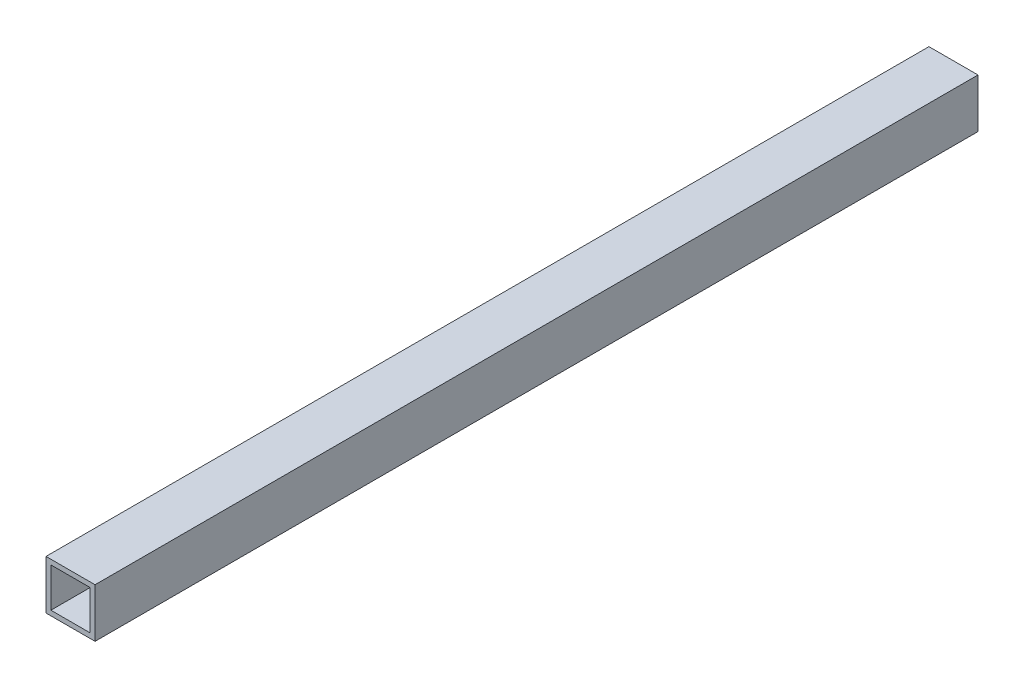
SolidWorks part; units mm, degrees
ref_plane "Płaszczyzna przednia" through (0, 0, 0) normal (0, 0, 1) x (1, 0, 0)
ref_plane "Płaszczyzna górna" through (0, 0, 0) normal (0, 1, 0) x (1, 0, 0)
ref_plane "Płaszczyzna prawa" through (0, 0, 0) normal (1, 0, 0) x (0, 0, -1)
sketch "Szkic1" plane through (0, 0, 0) normal (0, 0, 1) x (1, 0, 0)
  line L1 (-5, -5) -> (5, -5)
  line L2 (-5, -5) -> (-5, 5)
  line L3 (-5, 5) -> (5, 5)
  line L4 (5, -5) -> (5, 5)
  line L5 (-5, -5) -> (5, 5) construction
  line L6 (-5, 5) -> (5, -5) construction
  line L7 (-4, -4) -> (4, -4)
  line L8 (-4, -4) -> (-4, 4)
  line L9 (-4, 4) -> (4, 4)
  line L10 (4, -4) -> (4, 4)
  line L11 (-4, -4) -> (4, 4) construction
  line L12 (-4, 4) -> (4, -4) construction
  point P0 (0, 0)
  point P5 (0, 0)
  dimension "D1" = 10
  dimension "D2" = 8
extrude "Dodanie-wyciągnięcie1" add sketch "Szkic1" along normal blind 180
